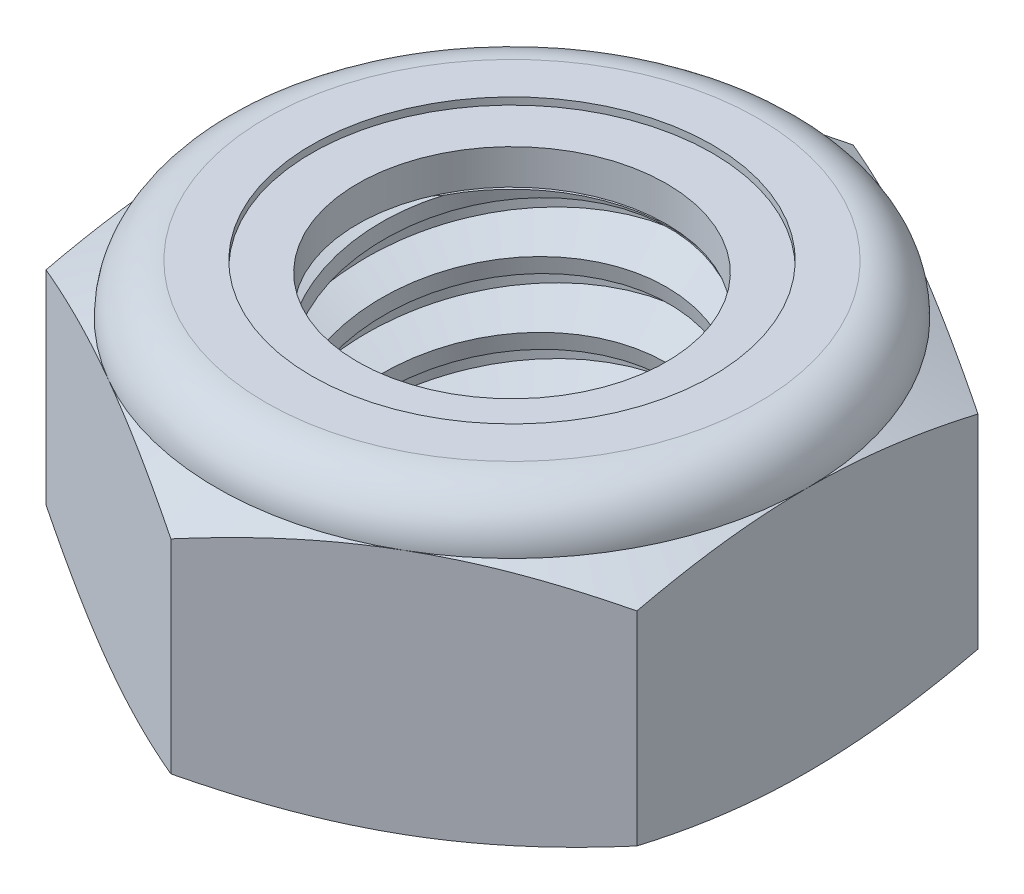
SolidWorks part; units mm, degrees
material "AISI 316 Annealed Stainless Steel Bar (SS)"
ref_plane "Front" through (0, 0, 0) normal (0, 0, 1) x (1, 0, 0)
ref_plane "Top" through (0, 0, 0) normal (0, 1, 0) x (1, 0, 0)
ref_plane "Right" through (0, 0, 0) normal (1, 0, 0) x (0, 0, -1)
sketch "Sketch1" plane through (0, 0, 0) normal (0, 1, 0) x (1, 0, 0)
  line L1 (0, 7.3323) -> (-6.35, 3.6662)
  line L2 (-6.35, 3.6662) -> (-6.35, -3.6662)
  line L3 (-6.35, -3.6662) -> (0, -7.3323)
  line L4 (0, -7.3323) -> (6.35, -3.6662)
  line L5 (6.35, -3.6662) -> (6.35, 3.6662)
  line L6 (6.35, 3.6662) -> (0, 7.3323)
  circle A0 centre (0, 0) radius 6.35 construction
  dimension "Hex Flats" = 12.7
extrude "Extrude1" add sketch "Sketch1" along normal blind 6.35
sketch "Sketch2" plane through (0, 0, 0) normal (1, 0, 0) x (0, 0, -1)
  line L0 (-3.9624, 0) -> (-3.9624, 6.35) construction
  line L1 (0, 0) -> (3.9624, 0)
  line L2 (0, 0) -> (0, 6.35)
  line L3 (0, 6.35) -> (3.9624, 6.35)
  line L4 (3.9624, 0) -> (3.9624, 6.35)
  line L5 (-3.6662, 6.35) -> (3.6662, 6.35) construction
  line L7 (0, -3.9624) -> (0, 0) construction
  dimension "Thread Dia" = 7.9248
revolve "Revolve1" add sketch "Sketch2" angle 360 about L7
sketch "Sketch3" plane through (0, 0, 0) normal (1, 0, 0) x (0, 0, -1)
  line L0 (3.9624, 6.35) -> (-3.9624, 6.35) construction
  line L1 (-3.9624, 6.35) -> (-3.9624, 4.9389) construction
  line L2 (-3.9624, 4.9389) -> (3.9624, 6.35) construction
  line L3 (3.9624, 6.35) -> (3.9933, 6.1763) construction
  line L4 (3.9933, 6.1763) -> (4.2098, 4.9607)
  line L5 (4.2098, 4.9607) -> (3.3805, 5.261)
  line L6 (3.3805, 5.261) -> (3.3187, 5.6083)
  line L7 (3.3187, 5.6083) -> (3.9933, 6.1763)
  line L8 (3.3496, 5.4346) -> (4.1015, 5.5685) construction
  line L9 (3.9624, 6.35) -> (3.9624, 5.5438) construction
  line L10 (3.9624, 5.5438) -> (-3.9624, 4.1327) construction
  line L11 (-3.9624, 4.1327) -> (-3.9624, 4.9389) construction
  line L12 (-0.2692, 6.35) -> (0.2692, 3.3264) construction
  line L13 (-3.9624, 0) -> (-3.9624, 6.35) construction
  line L14 (0, 6.35) -> (3.9624, 6.35) construction
  line L15 (3.9624, 0) -> (3.9624, 6.35) construction
  point P13 (0, 4.8382)
  dimension "D1" = 0.1764
  dimension "D2" = 0.3528
  dimension "Thread Pitch" = 1.4111
  dimension "D4" = 60
  dimension "D5" = 1.4111
revolve "Cut-Revolve1" cut sketch "Sketch3" angle 360 about L12
pattern_linear "LPattern1" count 5 spacing 1.4111 along (0, -1, 0) count 2 spacing 1.4111 along (0, 1, 0) of "Cut-Revolve1"
sketch "Sketch4" plane through (0, 0, 0) normal (1, 0, 0) x (0, 0, -1)
  line L0 (0, 6.35) -> (3.9624, 6.35)
  line L1 (3.9624, 6.35) -> (3.3187, 6.0498)
  line L2 (3.3187, 6.0498) -> (3.3187, 0.3002)
  line L3 (3.3187, 0.3002) -> (3.9624, 0)
  line L4 (3.9624, 0) -> (0, 0)
  line L5 (0, 0) -> (0, 6.35)
  line L6 (3.9624, 0) -> (3.9624, 6.35) construction
  line L7 (0, 6.35) -> (3.9624, 6.35) construction
  line L8 (0, 0) -> (3.9624, 0) construction
  line L9 (0, 0) -> (0, 6.35) construction
  line L10 (0, 6.35) -> (0, 7.0603) construction
  dimension "D1" = 25
revolve "Cut-Revolve2" cut sketch "Sketch4" angle 360 about L10
combine bodies "Combine1" operation type subtract main body 112 bodies to subtract 111
sketch "Sketch5" plane through (0, 0, 0) normal (1, 0, 0) x (0, 0, -1)
  line L0 (0, 0) -> (6.35, 0)
  line L1 (6.35, 0) -> (7.3323, 0.4581)
  line L2 (7.3323, 0.4581) -> (7.3323, 4.8336)
  line L3 (7.3323, 4.8336) -> (6.35, 5.2917)
  line L4 (5.2917, 6.35) -> (5.2917, 7.62)
  line L5 (5.2917, 7.62) -> (8.6023, 7.62)
  line L6 (8.6023, 7.62) -> (8.6023, -1.27)
  line L7 (8.6023, -1.27) -> (0, -1.27)
  line L8 (0, -1.27) -> (0, 0)
  line L9 (6.35, 5.2917) -> (6.35, 0) construction
  line L10 (0, 0) -> (3.9624, 0) construction
  line L13 (7.3323, 2.6458) -> (8.6023, 2.6458) construction
  line L14 (7.3323, 6.35) -> (7.3323, 0) construction
  line L15 (0, 0) -> (0, 7.62) construction
  line L20 (0, 7.62) -> (5.2917, 7.62) construction
  line L22 (0, 6.35) -> (3.9624, 6.35) construction
  arc A0 (6.35, 5.2917) -> (5.2917, 6.35) centre (5.2917, 5.2917) ccw
  dimension "D1" = 25
  dimension "D2" = 1.27
  dimension "D3" = 6.35
  dimension "D4" = 1.0583
revolve "Cut-Revolve3" cut sketch "Sketch5" angle 360 about L15
sketch "Sketch6" plane through (0, 0, 0) normal (1, 0, 0) x (0, 0, -1)
  line L0 (0, 5.2917) -> (6.1976, 5.2917)
  line L1 (5.2917, 6.1976) -> (4.3052, 6.1976)
  line L2 (0, 7.62) -> (0, 5.2917)
  line L3 (4.3052, 7.62) -> (0, 7.62)
  line L4 (0, 7.62) -> (5.2917, 7.62) construction
  line L5 (0, 0) -> (0, 7.62) construction
  line L6 (0, 7.62) -> (0, 44.323) construction
  line L7 (4.3052, 6.1976) -> (4.3052, 7.62)
  line L8 (5.2917, 6.35) -> (5.2917, 6.1976) construction
  line L9 (4.3052, 6.1976) -> (3.3187, 6.1976) construction
  line L10 (3.3187, 6.1976) -> (3.3187, 6.0498) construction
  arc A0 (6.1976, 5.2917) -> (5.2917, 6.1976) centre (5.2917, 5.2917) ccw
  arc A1 (6.35, 5.2917) -> (5.2917, 6.35) centre (5.2917, 5.2917) ccw construction
  dimension "D1" = 0.1524
revolve "Cut-Revolve4" cut sketch "Sketch6" angle 360 about L6
sketch "Sketch7" plane through (0, 0, 0) normal (1, 0, 0) x (0, 0, -1)
  line L0 (3.3187, 5.3679) -> (6.1179, 5.3679)
  line L1 (5.2917, 6.1214) -> (3.3187, 6.1214)
  line L2 (3.3187, 6.1214) -> (3.3187, 5.3679)
  line L3 (3.3187, 5.3679) -> (0, 5.3679) construction
  line L4 (0, 5.3679) -> (0, 6.1214) construction
  line L5 (0, 6.1214) -> (3.3187, 6.1214) construction
  line L6 (3.3187, 5.3679) -> (3.3187, 5.2917) construction
  line L7 (0, 5.2917) -> (6.1976, 5.2917) construction
  line L8 (5.2917, 6.1214) -> (5.2917, 6.1976) construction
  arc A0 (6.1179, 5.3679) -> (5.2917, 6.1214) centre (5.2917, 5.2917) ccw
  arc A2 (6.1976, 5.2917) -> (5.2917, 6.1976) centre (5.2917, 5.2917) ccw construction
  dimension "D1" = 0.0762
revolve "Revolve2" add sketch "Sketch7" angle 360 about L4
equation "\"D1@Sketch3\"=\"Thread Pitch@Sketch3\"/8"
equation "\"D2@Sketch3\"=\"Thread Pitch@Sketch3\"/4"
equation "\"D5@Sketch3\"=\"Thread Pitch@Sketch3\""
equation "\"D4@LPattern1\"=\"Thread Pitch@Sketch3\""
equation "\"D3@LPattern1\"=\"Thread Pitch@Sketch3\""
equation "\"D1@LPattern1\"=\"Height@Extrude1\"/\"Thread Pitch@Sketch3\""
equation "\"D4@Sketch5\"=\"Height@Extrude1\"/6"
